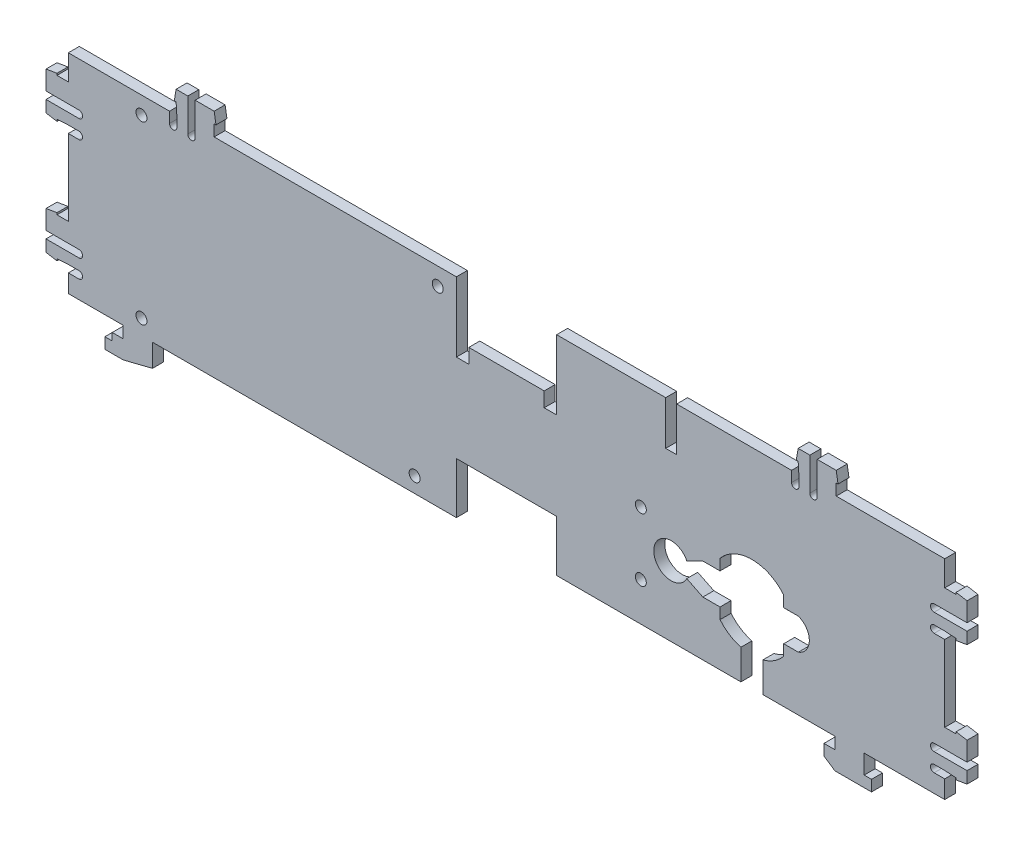
SolidWorks part; units mm, degrees
ref_plane "Front Plane" through (0, 0, 0) normal (0, 0, 1) x (1, 0, 0)
ref_plane "Top Plane" through (0, 0, 0) normal (0, 1, 0) x (1, 0, 0)
ref_plane "Right Plane" through (0, 0, 0) normal (1, 0, 0) x (0, 0, -1)
sketch "Sketch1" plane through (0, 0, 0) normal (0, 0, 1) x (1, 0, 0)
  line L0 (-10.3, 41) -> (-10.3, 45)
  line L1 (119.7542, 3) -> (97.7542, 3)
  line L2 (119.7542, 3) -> (119.7542, 60)
  line L3 (133, 60) -> (-133, 60) construction
  line L4 (-119.7542, 3) -> (-119.7542, 60)
  line L6 (133, 3) -> (-133, 3) construction
  line L7 (89.7542, 3) -> (13.7, 3)
  line L8 (-13.5, 16) -> (-13.5, 10) construction
  line L9 (-10.5, 16) -> (-10.5, 10) construction
  line L10 (-10.5, 16) -> (-13.5, 16) construction
  line L11 (-12, 16) -> (-12, 33.4397) construction
  line L12 (-10.3, 45) -> (10.3, 45)
  line L13 (10.3, 45) -> (10.3, 41)
  line L14 (-10.3, 41) -> (-13.7, 41)
  line L15 (-104.7542, 3) -> (-119.7542, 3)
  line L16 (-107.7542, -0.2) -> (-107.7542, -3.2)
  line L17 (-107.7542, -3.2) -> (-96.7542, -3.2)
  line L18 (-96.7542, 3) -> (-96.7542, -3.2)
  line L19 (-13.7, 60) -> (-119.7542, 60)
  line L20 (97.7542, 3) -> (97.7542, -3.2)
  line L21 (97.7542, -3.2) -> (86.7542, -3.2)
  line L22 (86.7542, -0.2) -> (86.7542, -3.2)
  line L23 (-13.7, 3) -> (-96.7542, 3)
  line L24 (13.7, 60) -> (13.7, 41)
  line L25 (13.7, 41) -> (10.3, 41)
  line L26 (-13.7, 60) -> (-13.7, 41)
  line L27 (-10.5, 10) -> (-13.5, 10) construction
  line L28 (13.7, 3) -> (13.7, 17)
  line L29 (-10.5, 41) -> (-13.5, 41) construction
  line L30 (-13.7, 3) -> (-13.7, 17)
  line L31 (-13.5, 41) -> (-13.5, 35) construction
  line L32 (0, 0) -> (-112.5227, 0) construction
  line L33 (-89.7542, 0) -> (-89.7542, -3.2) construction
  line L34 (104.7542, 0) -> (104.7542, -3.2) construction
  line L35 (0, 0) -> (0, 75.3204) construction
  line L36 (0, 60) -> (0, 249.4547) construction
  line L38 (104.7542, -3.2) -> (97.7542, -3.2) construction
  line L39 (119.7542, 60) -> (46.5, 60)
  line L40 (-89.7542, -3.2) -> (-96.7542, -3.2) construction
  line L51 (-13.7, 17) -> (13.7, 17)
  line L65 (43.5, 60) -> (43.5, 48)
  line L66 (43.5, 48) -> (46.5, 48)
  line L67 (46.5, 48) -> (46.5, 60)
  line L68 (43.5, 60) -> (13.7, 60)
  line L69 (-107.7542, -0.2) -> (-104.7542, -0.2)
  line L71 (-104.7542, -0.2) -> (-104.7542, 3)
  line L72 (-104.7542, 0) -> (-104.7542, 3) construction
  line L74 (86.7542, -0.2) -> (89.7542, -0.2)
  line L75 (89.7542, -0.2) -> (89.7542, 3)
  line L78 (89.7542, 0) -> (89.7542, 3) construction
  dimension "D1" = 3
  dimension "D2" = 0.2
  dimension "D3" = 4
  dimension "D4" = 1
  dimension "D5" = 12
  dimension "D6" = 0.2
  dimension "D7" = 3
  dimension "D8" = 8
extrude "Boss-Extrude1" add sketch "Sketch1" along normal up to vertex (3 mm away)
sketch "Sketch2" plane through (0, 0, 3) normal (0, 0, 1) x (1, 0, 0)
  line L0 (58.3561, 26.4122) -> (53.6571, 26.4122)
  line L1 (53.6571, 26.4122) -> (49.2615, 24.2481)
  line L2 (53.6571, 17.8878) -> (49.2615, 20.0519)
  line L3 (53.6571, 17.8878) -> (58.3561, 17.8878)
  line L4 (53.6571, 18.6575) -> (53.6571, 19.61) construction
  line L5 (64.0561, 11.2054) -> (64.0561, 3)
  line L6 (13.7, 3) -> (89.7542, 3) construction
  line L7 (75.7561, 29.4122) -> (75.7561, 26.4122)
  line L8 (75.7561, 26.4122) -> (79.7561, 26.4122)
  line L9 (64.0561, 3) -> (70.0561, 3)
  line L10 (70.0561, 3) -> (70.0561, 11.2054)
  line L13 (58.3561, 29.4122) -> (58.3561, 14.8878) construction
  line L14 (58.3561, 17.8878) -> (58.3561, 14.8878)
  line L19 (75.7561, 14.8878) -> (75.7561, 17.8878)
  line L20 (75.7561, 17.8878) -> (79.7561, 17.8878)
  line L21 (58.3561, 29.4122) -> (58.3561, 26.4122)
  arc A0 (49.2615, 24.2481) -> (49.2615, 20.0519) centre (45, 22.15) ccw
  arc A1 (58.3561, 14.8878) -> (64.0561, 11.2054) centre (67.0561, 22.102) ccw
  arc A2 (75.7561, 29.4122) -> (58.3561, 29.4122) centre (67.0561, 22.198) ccw
  arc A3 (75.7561, 14.8878) -> (70.0561, 11.2054) centre (67.0561, 22.102) cw
  arc A7 (58.3561, 14.8878) -> (75.7561, 14.8878) centre (67.0561, 22.102) ccw construction
  arc A10 (79.7561, 26.4122) -> (79.7561, 17.8878) centre (78.2283, 22.15) cw
  dimension "D1" = 4.75
  dimension "D2" = 11.302
  dimension "D4" = 3
  dimension "D3" = 17.4
  dimension "D5" = 4
  dimension "D6" = 6
  dimension "D7" = 3
extrude "motor slot" cut sketch "Sketch2" against normal up to next
sketch "Sketch3" plane through (0, 0, 3) normal (0, 0, 1) x (1, 0, 0)
  circle A0 centre (36.7079, 13.55) radius 1.5
  circle A1 centre (36.7079, 30.75) radius 1.5
  dimension "D1" = 3
extrude "motor mounting holes" cut sketch "Sketch3" against normal up to next
sketch "Sketch4" plane through (0, 0, 0) normal (0, 0, -1) x (-1, 0, 0)
  line L18 (0, 0) -> (0, 111.2073) construction
  line B0 (122.8542, 42.7) -> (119.7542, 42.9)
  line B1 (119.7542, 40.9) -> (119.7542, 38.9)
  line B2 (122.8542, 53.1) -> (119.7542, 53.1)
  line B3 (119.7542, 53.1) -> (119.7542, 55.1)
  line B4 (116.8542, 45.9) -> (125.8542, 45.9)
  line B5 (125.8542, 53.1) -> (125.8542, 47.9)
  line B6 (116.8542, 47.9) -> (128.6542, 47.9) construction
  line B7 (119.7542, 42.9) -> (116.8542, 42.9)
  line B8 (116.8542, 40.9) -> (119.7542, 40.9)
  line B9 (122.8542, 42.7) -> (122.8542, 42.2)
  line B10 (122.8542, 42.2) -> (125.8542, 42.7)
  line B11 (125.8542, 45.9) -> (125.8542, 42.7)
  line B12 (125.8542, 47.9) -> (116.8542, 47.9)
  line B13 (122.8542, 53.1) -> (122.8542, 53.6)
  line B14 (122.8542, 53.6) -> (125.8542, 53.1)
  arc B15 (116.8542, 47.9) -> (116.8542, 45.9) centre (116.8542, 46.9) ccw
  arc B16 (116.8542, 42.9) -> (116.8542, 40.9) centre (116.8542, 41.9) ccw
  line B17 (122.7542, 55.1) -> (122.7542, 38.9) construction
  line B18 (122.7542, 55.1) -> (119.7542, 55.1) construction
  line B19 (116.8542, 46.9) -> (116.8542, 41.9) construction
  line B20 (119.7542, 53.1) -> (119.7542, 40.9) construction
  line B21 (119.7542, 55.1) -> (112.7542, 55.1)
  line B22 (112.7542, 55.1) -> (112.7542, 38.9)
  line B23 (112.7542, 38.9) -> (119.7542, 38.9)
  line B24 (122.8542, 9.7) -> (119.7542, 9.9)
  line B25 (119.7542, 7.9) -> (119.7542, 5.9)
  line B26 (122.8542, 20.1) -> (119.7542, 20.1)
  line B27 (119.7542, 20.1) -> (119.7542, 22.1)
  line B28 (116.8542, 12.9) -> (125.8542, 12.9)
  line B29 (125.8542, 20.1) -> (125.8542, 14.9)
  line B30 (116.8542, 14.9) -> (128.6542, 14.9) construction
  line B31 (119.7542, 9.9) -> (116.8542, 9.9)
  line B32 (116.8542, 7.9) -> (119.7542, 7.9)
  line B33 (122.8542, 9.7) -> (122.8542, 9.2)
  line B34 (122.8542, 9.2) -> (125.8542, 9.7)
  line B35 (125.8542, 12.9) -> (125.8542, 9.7)
  line B36 (125.8542, 14.9) -> (116.8542, 14.9)
  line B37 (122.8542, 20.1) -> (122.8542, 20.6)
  line B38 (122.8542, 20.6) -> (125.8542, 20.1)
  arc B39 (116.8542, 14.9) -> (116.8542, 12.9) centre (116.8542, 13.9) ccw
  arc B40 (116.8542, 9.9) -> (116.8542, 7.9) centre (116.8542, 8.9) ccw
  line B41 (122.7542, 22.1) -> (122.7542, 5.9) construction
  line B42 (122.7542, 22.1) -> (119.7542, 22.1) construction
  line B43 (116.8542, 13.9) -> (116.8542, 8.9) construction
  line B44 (122.7542, 5.9) -> (119.7542, 5.9) construction
  line B45 (119.7542, 20.1) -> (119.7542, 7.9) construction
  line B46 (119.7542, 22.1) -> (112.7542, 22.1)
  line B47 (112.7542, 22.1) -> (112.7542, 5.9)
  line B48 (112.7542, 5.9) -> (119.7542, 5.9)
  line B49 (-122.8542, 9.7) -> (-119.7542, 9.9)
  line B50 (-119.7542, 7.9) -> (-119.7542, 5.9)
  line B51 (-122.8542, 20.1) -> (-119.7542, 20.1)
  line B52 (-119.7542, 20.1) -> (-119.7542, 22.1)
  line B53 (-116.8542, 12.9) -> (-125.8542, 12.9)
  line B54 (-125.8542, 20.1) -> (-125.8542, 14.9)
  line B55 (-119.7542, 9.9) -> (-116.8542, 9.9)
  line B56 (-116.8542, 7.9) -> (-119.7542, 7.9)
  line B57 (-122.8542, 9.7) -> (-122.8542, 9.2)
  line B58 (-122.8542, 9.2) -> (-125.8542, 9.7)
  line B59 (-125.8542, 12.9) -> (-125.8542, 9.7)
  line B60 (-125.8542, 14.9) -> (-116.8542, 14.9)
  line B61 (-122.8542, 20.1) -> (-122.8542, 20.6)
  line B62 (-122.8542, 20.6) -> (-125.8542, 20.1)
  arc B63 (-116.8542, 14.9) -> (-116.8542, 12.9) centre (-116.8542, 13.9) cw
  arc B64 (-116.8542, 9.9) -> (-116.8542, 7.9) centre (-116.8542, 8.9) cw
  line B65 (-119.7542, 22.1) -> (-112.7542, 22.1)
  line B66 (-112.7542, 22.1) -> (-112.7542, 5.9)
  line B67 (-112.7542, 5.9) -> (-119.7542, 5.9)
  line B68 (-122.8542, 42.7) -> (-119.7542, 42.9)
  line B69 (-119.7542, 40.9) -> (-119.7542, 38.9)
  line B70 (-122.8542, 53.1) -> (-119.7542, 53.1)
  line B71 (-119.7542, 53.1) -> (-119.7542, 55.1)
  line B72 (-116.8542, 45.9) -> (-125.8542, 45.9)
  line B73 (-125.8542, 53.1) -> (-125.8542, 47.9)
  line B74 (-119.7542, 42.9) -> (-116.8542, 42.9)
  line B75 (-116.8542, 40.9) -> (-119.7542, 40.9)
  line B76 (-122.8542, 42.7) -> (-122.8542, 42.2)
  line B77 (-122.8542, 42.2) -> (-125.8542, 42.7)
  line B78 (-125.8542, 45.9) -> (-125.8542, 42.7)
  line B79 (-125.8542, 47.9) -> (-116.8542, 47.9)
  line B80 (-122.8542, 53.1) -> (-122.8542, 53.6)
  line B81 (-122.8542, 53.6) -> (-125.8542, 53.1)
  arc B82 (-116.8542, 47.9) -> (-116.8542, 45.9) centre (-116.8542, 46.9) cw
  arc B83 (-116.8542, 42.9) -> (-116.8542, 40.9) centre (-116.8542, 41.9) cw
  line B84 (-119.7542, 55.1) -> (-112.7542, 55.1)
  line B85 (-112.7542, 55.1) -> (-112.7542, 38.9)
  line B86 (-112.7542, 38.9) -> (-119.7542, 38.9)
sketch_block_instance "external-tooth-tab-1"
sketch_block "external-tooth-tab" parameters "D1"=1, "D2"=6, "D3"=3, "D4"=3.1, "D5"=10.2, "D6"=0.2, "D7"=0.5, "D8"=3, "D9"=4.3072, "D10"=5, "D11"=0.5
sketch_block_instance "external-tooth-tab-3"
sketch_block_instance "external-tooth-tab-4"
sketch_block_instance "external-tooth-tab-5"
sketch "Sketch5" plane through (0, 0, 0) normal (0, 0, -1) x (-1, 0, 0)
  circle A0 centre (25.1045, 7.1977) radius 1.5
  circle A1 centre (99.7684, 7.1977) radius 1.5
  circle A2 centre (99.7684, 55.2289) radius 1.5
  circle A3 centre (18.7971, 55.2289) radius 1.5
  dimension "D2" = 3
extrude "Arduino mounting holes" cut sketch "Sketch5" against normal up to next
extrude "front and back plate tabs" add sketch "Sketch4" against normal up to surface (3 mm away) up to face at (-17.2971, 55.2289, 3)
sketch "Sketch6" plane through (0, 0, 0) normal (0, 0, -1) x (-1, 0, 0)
  line L0 (116.8542, 45.9) -> (125.8542, 45.9) construction
  line L1 (125.8542, 47.9) -> (116.8542, 47.9) construction
  line L2 (119.7542, 42.9) -> (116.8542, 42.9) construction
  line L3 (116.8542, 40.9) -> (119.7542, 40.9) construction
  line L4 (116.8542, 45.9) -> (125.8542, 45.9)
  line L5 (125.8542, 47.9) -> (116.8542, 47.9)
  line L6 (119.7542, 42.9) -> (116.8542, 42.9)
  line L7 (116.8542, 40.9) -> (119.7542, 40.9)
  line L8 (119.7542, 42.9) -> (119.7542, 40.9)
  line L9 (125.8542, 47.9) -> (125.8542, 45.9)
  line L10 (116.8542, 12.9) -> (125.8542, 12.9) construction
  line L11 (125.8542, 14.9) -> (116.8542, 14.9) construction
  line L12 (119.7542, 9.9) -> (116.8542, 9.9) construction
  line L13 (116.8542, 7.9) -> (119.7542, 7.9) construction
  line L14 (116.8542, 12.9) -> (125.8542, 12.9)
  line L15 (125.8542, 14.9) -> (116.8542, 14.9)
  line L16 (119.7542, 9.9) -> (116.8542, 9.9)
  line L17 (116.8542, 7.9) -> (119.7542, 7.9)
  line L18 (119.7542, 7.9) -> (119.7542, 9.9)
  line L19 (125.8542, 12.9) -> (125.8542, 14.9)
  line L20 (0, 0) -> (0, 51.7039) construction
  line L21 (0, 0) -> (0, 111.2073) construction
  line L22 (-125.8542, 12.9) -> (-125.8542, 14.9)
  line L23 (-119.7542, 7.9) -> (-119.7542, 9.9)
  line L24 (-116.8542, 7.9) -> (-119.7542, 7.9)
  line L25 (-119.7542, 9.9) -> (-116.8542, 9.9)
  line L26 (-125.8542, 14.9) -> (-116.8542, 14.9)
  line L27 (-116.8542, 12.9) -> (-125.8542, 12.9)
  line L28 (-125.8542, 47.9) -> (-125.8542, 45.9)
  line L29 (-119.7542, 42.9) -> (-119.7542, 40.9)
  line L30 (-116.8542, 40.9) -> (-119.7542, 40.9)
  line L31 (-119.7542, 42.9) -> (-116.8542, 42.9)
  line L32 (-125.8542, 47.9) -> (-116.8542, 47.9)
  line L33 (-116.8542, 45.9) -> (-125.8542, 45.9)
  arc A0 (116.8542, 47.9) -> (116.8542, 45.9) centre (116.8542, 46.9) ccw construction
  arc A1 (116.8542, 42.9) -> (116.8542, 40.9) centre (116.8542, 41.9) ccw construction
  arc A2 (116.8542, 47.9) -> (116.8542, 45.9) centre (116.8542, 46.9) ccw
  arc A3 (116.8542, 42.9) -> (116.8542, 40.9) centre (116.8542, 41.9) ccw
  arc A4 (116.8542, 14.9) -> (116.8542, 12.9) centre (116.8542, 13.9) ccw construction
  arc A5 (116.8542, 9.9) -> (116.8542, 7.9) centre (116.8542, 8.9) ccw construction
  arc A6 (116.8542, 14.9) -> (116.8542, 12.9) centre (116.8542, 13.9) ccw
  arc A7 (116.8542, 9.9) -> (116.8542, 7.9) centre (116.8542, 8.9) ccw
  arc A8 (-116.8542, 9.9) -> (-116.8542, 7.9) centre (-116.8542, 8.9) cw
  arc A9 (-116.8542, 14.9) -> (-116.8542, 12.9) centre (-116.8542, 13.9) cw
  arc A10 (-116.8542, 42.9) -> (-116.8542, 40.9) centre (-116.8542, 41.9) cw
  arc A11 (-116.8542, 47.9) -> (-116.8542, 45.9) centre (-116.8542, 46.9) cw
extrude "front and back tab relief" cut sketch "Sketch6" against normal up to next
sketch "Sketch7" plane through (0, 0, 0) normal (0, 0, -1) x (-1, 0, 0)
  line L1 (0, 0) -> (0, 79.0599) construction
  line L2 (-85, 76.6573) -> (-85, 60) construction
  line B0 (90.3, 63.1) -> (90.1, 60)
  line B1 (92.1, 60) -> (94.1, 60)
  line B2 (79.9, 63.1) -> (79.9, 60)
  line B3 (79.9, 60) -> (77.9, 60)
  line B4 (87.1, 57.1) -> (87.1, 66.1)
  line B5 (79.9, 66.1) -> (85.1, 66.1)
  line B6 (85.1, 57.1) -> (85.1, 68.9) construction
  line B7 (90.1, 60) -> (90.1, 57.1)
  line B8 (92.1, 57.1) -> (92.1, 60)
  line B9 (90.3, 63.1) -> (90.8, 63.1)
  line B10 (90.8, 63.1) -> (90.3, 66.1)
  line B11 (87.1, 66.1) -> (90.3, 66.1)
  line B12 (85.1, 66.1) -> (85.1, 57.1)
  line B13 (79.9, 63.1) -> (79.4, 63.1)
  line B14 (79.4, 63.1) -> (79.9, 66.1)
  arc B15 (85.1, 57.1) -> (87.1, 57.1) centre (86.1, 57.1) ccw
  arc B16 (90.1, 57.1) -> (92.1, 57.1) centre (91.1, 57.1) ccw
  line B17 (77.9, 63) -> (94.1, 63) construction
  line B18 (77.9, 63) -> (77.9, 60) construction
  line B19 (90.3, 63.1) -> (90.3, 66.1) construction
  line B20 (86.1, 57.1) -> (91.1, 57.1) construction
  line B21 (79.9, 60) -> (92.1, 60) construction
  line B22 (77.9, 60) -> (77.9, 53)
  line B23 (77.9, 53) -> (94.1, 53)
  line B24 (94.1, 53) -> (94.1, 60)
  line B25 (-79.7, 63.1) -> (-79.9, 60)
  line B26 (-77.9, 60) -> (-75.9, 60)
  line B27 (-90.1, 63.1) -> (-90.1, 60)
  line B28 (-90.1, 60) -> (-92.1, 60)
  line B29 (-82.9, 57.1) -> (-82.9, 66.1)
  line B30 (-90.1, 66.1) -> (-84.9, 66.1)
  line B31 (-84.9, 57.1) -> (-84.9, 68.9) construction
  line B32 (-79.9, 60) -> (-79.9, 57.1)
  line B33 (-77.9, 57.1) -> (-77.9, 60)
  line B34 (-79.7, 63.1) -> (-79.2, 63.1)
  line B35 (-79.2, 63.1) -> (-79.7, 66.1)
  line B36 (-82.9, 66.1) -> (-79.7, 66.1)
  line B37 (-84.9, 66.1) -> (-84.9, 57.1)
  line B38 (-90.1, 63.1) -> (-90.6, 63.1)
  line B39 (-90.6, 63.1) -> (-90.1, 66.1)
  arc B40 (-84.9, 57.1) -> (-82.9, 57.1) centre (-83.9, 57.1) ccw
  arc B41 (-79.9, 57.1) -> (-77.9, 57.1) centre (-78.9, 57.1) ccw
  line B42 (-92.1, 63) -> (-75.9, 63) construction
  line B43 (-83.9, 57.1) -> (-78.9, 57.1) construction
  line B44 (-75.9, 63) -> (-75.9, 60) construction
  line B45 (-90.1, 60) -> (-77.9, 60) construction
  line B46 (-92.1, 60) -> (-92.1, 53)
  line B47 (-92.1, 53) -> (-75.9, 53)
  line B48 (-75.9, 53) -> (-75.9, 60)
sketch_block_instance "external-tooth-tab-8"
sketch_block_instance "external-tooth-tab-10"
extrude "top plate tabs" add sketch "Sketch7" against normal up to surface (3 mm away) up to face at (11.5819, 26.2629, 3)
sketch "Sketch8" plane through (0, 0, 0) normal (0, 0, -1) x (-1, 0, 0)
  line L0 (-84.9, 66.1) -> (-84.9, 57.1) construction
  line L1 (-82.9, 57.1) -> (-82.9, 66.1) construction
  line L2 (-79.9, 60) -> (-79.9, 57.1) construction
  line L3 (-77.9, 57.1) -> (-77.9, 60) construction
  line L4 (85.1, 66.1) -> (85.1, 57.1) construction
  line L5 (87.1, 57.1) -> (87.1, 66.1) construction
  line L6 (90.1, 60) -> (90.1, 57.1) construction
  line L7 (92.1, 57.1) -> (92.1, 60) construction
  line L8 (-84.9, 66.1) -> (-84.9, 57.1)
  line L9 (-82.9, 57.1) -> (-82.9, 66.1)
  line L10 (-79.9, 60) -> (-79.9, 57.1)
  line L11 (-77.9, 57.1) -> (-77.9, 60)
  line L12 (85.1, 66.1) -> (85.1, 57.1)
  line L13 (87.1, 57.1) -> (87.1, 66.1)
  line L14 (90.1, 60) -> (90.1, 57.1)
  line L15 (92.1, 57.1) -> (92.1, 60)
  line L16 (90.1, 60) -> (92.1, 60)
  line L17 (85.1, 66.1) -> (87.1, 66.1)
  line L18 (-84.9, 66.1) -> (-82.9, 66.1)
  line L19 (-79.9, 60) -> (-77.9, 60)
  arc A0 (-84.9, 57.1) -> (-82.9, 57.1) centre (-83.9, 57.1) ccw construction
  arc A1 (-79.9, 57.1) -> (-77.9, 57.1) centre (-78.9, 57.1) ccw construction
  arc A2 (85.1, 57.1) -> (87.1, 57.1) centre (86.1, 57.1) ccw construction
  arc A3 (90.1, 57.1) -> (92.1, 57.1) centre (91.1, 57.1) ccw construction
  arc A4 (-84.9, 57.1) -> (-82.9, 57.1) centre (-83.9, 57.1) ccw
  arc A5 (-79.9, 57.1) -> (-77.9, 57.1) centre (-78.9, 57.1) ccw
  arc A6 (85.1, 57.1) -> (87.1, 57.1) centre (86.1, 57.1) ccw
  arc A7 (90.1, 57.1) -> (92.1, 57.1) centre (91.1, 57.1) ccw
extrude "top plate tab relief" cut sketch "Sketch8" against normal up to next
sketch "Sketch9" plane through (0, 0, 0) normal (0, 0, -1) x (-1, 0, 0)
  line L0 (107.7542, -2.2) -> (109.7542, -2.2)
  line L1 (107.7542, -0.2) -> (107.7542, -3.2) construction
  line L2 (109.7542, -2.2) -> (109.7542, -5.2)
  line L3 (109.7542, -5.2) -> (104.7542, -5.2)
  line L4 (96.7542, -3.2) -> (107.7542, -3.2)
  line L5 (107.7542, -3.2) -> (96.7542, -3.2) construction
  line L6 (107.7542, -3.2) -> (107.7542, -2.2)
  line L7 (104.7542, -0.2) -> (107.7542, -0.2) construction
  line L8 (104.7542, -5.2) -> (96.7542, -3.2)
  line L9 (104.7542, 3) -> (104.7542, -0.2) construction
  line L10 (-97.7542, -2.2) -> (-99.7542, -2.2)
  line L11 (-97.7542, -3.2) -> (-97.7542, 3) construction
  line L12 (-99.7542, -2.2) -> (-99.7542, -5.2)
  line L13 (-99.7542, -5.2) -> (-89.7542, -5.2)
  line L14 (-89.7542, -5.2) -> (-86.7542, -3.2)
  line L15 (-86.7542, -3.2) -> (-97.7542, -3.2)
  line L16 (-97.7542, -3.2) -> (-97.7542, -2.2)
  line L17 (-89.7542, 3) -> (-89.7542, -0.2) construction
  line L18 (-89.7542, -0.2) -> (-86.7542, -0.2) construction
  dimension "D1" = 2
  dimension "D2" = 2
  dimension "D3" = 3
  dimension "D4" = 2
  dimension "D5" = 3
  dimension "D6" = 2
extrude "drawstring hooks" add sketch "Sketch9" against normal up to surface (3 mm away) up to face at (8.7529, 33.8237, 3)
